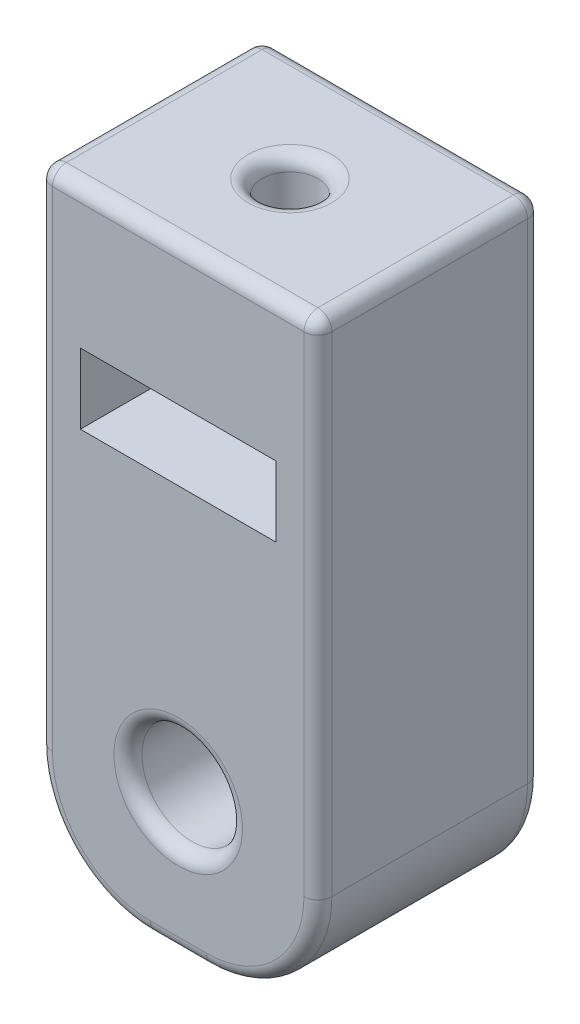
SolidWorks part; units mm, degrees
ref_plane "Front Plane" through (0, 0, 0) normal (0, 0, 1) x (1, 0, 0)
ref_plane "Top Plane" through (0, 0, 0) normal (0, 1, 0) x (1, 0, 0)
ref_plane "Right Plane" through (0, 0, 0) normal (1, 0, 0) x (0, 0, -1)
sketch "Sketch1" plane through (0, 0, 0) normal (0, 0, 1) x (1, 0, 0)
  line L1 (0, 0) -> (12.7, 0)
  line L2 (0, 0) -> (0, 27.94)
  line L3 (0, 27.94) -> (12.7, 27.94)
  line L4 (12.7, 0) -> (12.7, 27.94)
  circle A0 centre (6.35, 6.35) radius 2.286
  point P7 (6.35, 0)
  dimension "D2" = 4.572
  dimension "D1" = 27.94
  dimension "D3" = 6.35
  dimension "D4" = 12.7
extrude "Boss-Extrude1" add sketch "Sketch1" along normal blind 10.16
sketch "Sketch2" plane through (0, 27.94, 0) normal (0, 1, 0) x (1, 0, 0)
  line L0 (12.7, 0) -> (0, 0) construction
  line L1 (0, -10.16) -> (0, 0) construction
  circle A0 centre (6.35, -5.08) radius 1.27
  point P2 (6.35, 0)
  point P3 (0, -5.08)
  dimension "D1" = 2.54
extrude "Cut-Extrude1" cut sketch "Sketch2" against normal blind 15.24
fillet "Fillet2" radius 5.08 2 edges at (12.7, 0, 5.08) (0, 0, 5.08)
fillet "Fillet1" radius 0.635 17 edges at (8.636, 6.35, 0) (6.35, 0, 0) (0, 16.51, 0) (12.7, 16.51, 0) (12.7, 27.94, 5.08) (0, 27.94, 5.08) (6.35, 27.94, 0) (6.35, 27.94, 6.35) (8.636, 6.35, 10.16) (6.35, 27.94, 10.16) (12.7, 16.51, 10.16) (6.35, 0, 10.16) (0, 16.51, 10.16) (1.4879, 1.4879, 0) (11.2121, 1.4879, 0) (11.2121, 1.4879, 10.16) (1.4879, 1.4879, 10.16)
sketch "Sketch3" plane through (0, 0, 0) normal (0, 0, -1) x (-1, 0, 0)
  line L0 (-12.065, 27.94) -> (-0.635, 27.94) construction
  line L2 (-10.795, 21.59) -> (-1.905, 21.59)
  line L3 (-10.795, 21.59) -> (-10.795, 18.3947)
  line L4 (-10.795, 18.3947) -> (-1.905, 18.3947)
  line L5 (-1.905, 21.59) -> (-1.905, 18.3947)
  point P0 (-6.35, 27.94)
  point P7 (-6.35, 21.59)
  dimension "D1" = 6.35
  dimension "D2" = 3.1953
  dimension "D3" = 8.89
extrude "Cut-Extrude2" cut sketch "Sketch3" against normal through all
